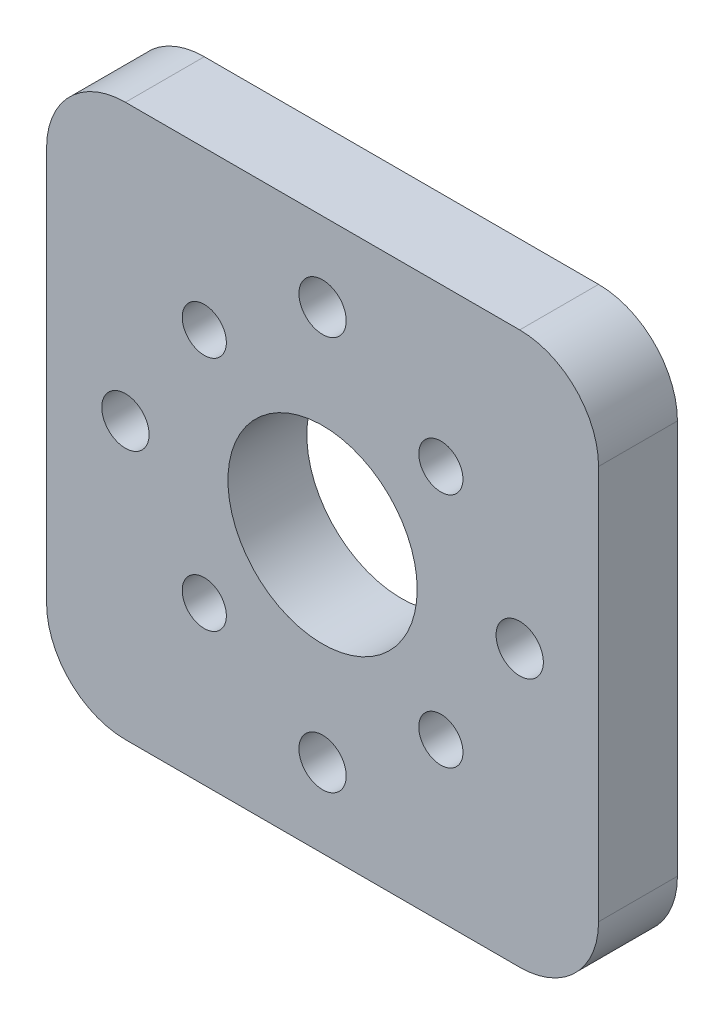
SolidWorks part; units mm, degrees
ref_plane "前视基准面" through (0, 0, 0) normal (0, 0, 1) x (1, 0, 0)
ref_plane "上视基准面" through (0, 0, 0) normal (0, 1, 0) x (1, 0, 0)
ref_plane "右视基准面" through (0, 0, 0) normal (1, 0, 0) x (0, 0, -1)
other "Configuration Table"
sketch "草图1" plane through (0, 0, 0) normal (0, 0, 1) x (1, 0, 0)
  line L1 (-7.5, -7.5) -> (7.5, -7.5) construction
  line L2 (-7.5, -7.5) -> (-7.5, 7.5) construction
  line L3 (-7.5, 7.5) -> (7.5, 7.5) construction
  line L4 (7.5, -7.5) -> (7.5, 7.5) construction
  line L5 (-7.5, -7.5) -> (7.5, 7.5) construction
  line L6 (-7.5, 7.5) -> (7.5, -7.5) construction
  line L7 (-17.5, 17.5) -> (17.5, 17.5)
  line L8 (-17.5, 17.5) -> (-17.5, -17.5)
  line L9 (-17.5, -17.5) -> (17.5, -17.5)
  line L10 (17.5, 17.5) -> (17.5, -17.5)
  line L11 (-17.5, 17.5) -> (17.5, -17.5) construction
  line L12 (-17.5, -17.5) -> (17.5, 17.5) construction
  circle A0 centre (0, 0) radius 12.5 construction
  circle A1 centre (0, 0) radius 17.5 construction
  circle A2 centre (0, 12.5) radius 1.5
  circle A3 centre (12.5, 0) radius 1.5
  circle A4 centre (0, -12.5) radius 1.5
  circle A5 centre (-12.5, 0) radius 1.5
  circle A6 centre (0, 0) radius 6
  circle A7 centre (-7.5, 7.5) radius 1.4
  circle A8 centre (7.5, 7.5) radius 1.4
  circle A9 centre (7.5, -7.5) radius 1.4
  circle A10 centre (-7.5, -7.5) radius 1.4
  dimension "D1" = 25
  dimension "D2" = 35
  dimension "D3" = 3
  dimension "D4" = 12
  dimension "D5" = 2.8
  dimension "15" = 15
extrude "凸台-拉伸1" add sketch "草图1" along normal blind 5
fillet "圆角1" radius 5 4 edges at (17.5, -17.5, 2.5) (-17.5, 17.5, 2.5) (17.5, 17.5, 2.5) (-17.5, -17.5, 2.5)
